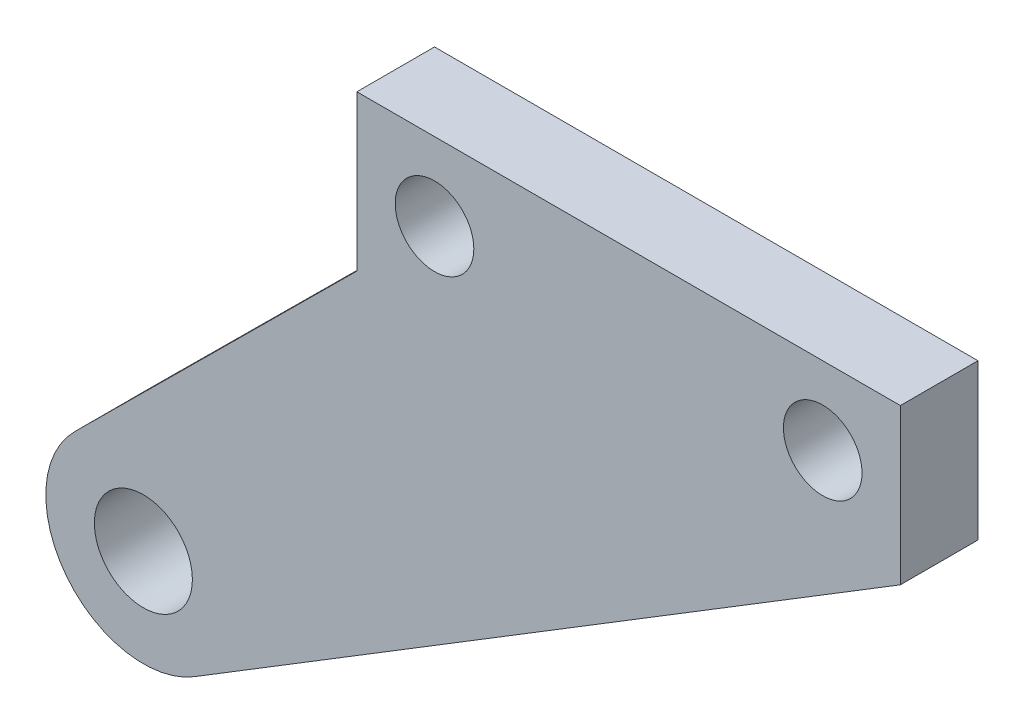
SolidWorks part; units mm, degrees
ref_plane "前视基准面" through (0, 0, 0) normal (0, 0, 1) x (1, 0, 0)
ref_plane "上视基准面" through (0, 0, 0) normal (0, 1, 0) x (1, 0, 0)
ref_plane "右视基准面" through (0, 0, 0) normal (1, 0, 0) x (0, 0, -1)
other "Configuration Table"
sketch "草图1" plane through (0, 0, 0) normal (0, 0, 1) x (1, 0, 0)
  line L0 (-10, 0) -> (10, 0) construction
  line L1 (-14, 4) -> (14, 4)
  line L2 (14, 4) -> (14, -4)
  line L3 (14, -4) -> (-22.3749, -26.2848)
  line L5 (-14, 4) -> (-14, -4)
  line L6 (-14, -4) -> (-28.5401, -18.4338)
  circle A0 centre (10, 0) radius 2.025
  circle A1 centre (-10, 0) radius 2.025
  circle A2 centre (-25, -22) radius 2.525
  arc A3 (-28.5401, -18.4338) -> (-22.3749, -26.2848) centre (-25, -22) ccw
  point P4 (0, 0)
  dimension "D2" = 4.05
  dimension "D3" = 5.05
  dimension "D4" = 2.5
  dimension "D1" = 20
  dimension "D5" = 4
  dimension "D6" = 4
  dimension "D7" = 15
  dimension "D8" = 22
  dimension "D9" = 4
  dimension "D10" = 4
  dimension "D11" = 4
extrude "凸台-拉伸1" add sketch "草图1" along normal mid plane 4
